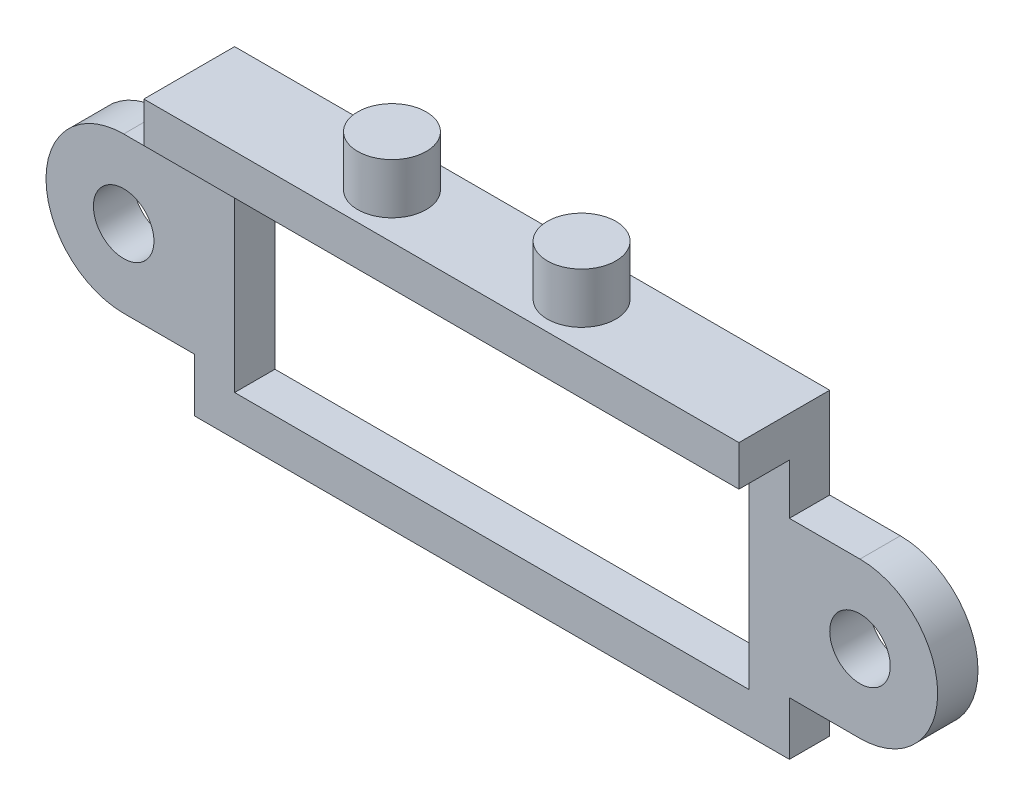
SolidWorks part; units mm, degrees
ref_plane "Front Plane" through (0, 0, 0) normal (0, 0, 1) x (1, 0, 0)
ref_plane "Top Plane" through (0, 0, 0) normal (0, 1, 0) x (1, 0, 0)
ref_plane "Right Plane" through (0, 0, 0) normal (1, 0, 0) x (0, 0, -1)
sketch "Sketch1" plane through (0, 0, 0) normal (0, 0, 1) x (1, 0, 0)
  line L0 (-14.75, 5.675) -> (-14.75, 1.175)
  line L1 (-14.75, -9.175) -> (14.75, -9.175)
  line L2 (-14.75, -6.525) -> (-14.75, -9.175)
  line L3 (-14.75, 5.675) -> (14.75, 5.675)
  line L4 (14.75, 5.675) -> (14.75, 1.175)
  line L5 (-14.75, 1.175) -> (-18.25, 1.175)
  line L6 (-16.75, -2.675) -> (-16.75, -5.5492) construction
  line L7 (-14.75, -6.525) -> (-18.25, -6.525)
  line L8 (0, 5.675) -> (0, -9.175) construction
  line L9 (14.75, 1.175) -> (18.25, 1.175)
  line L10 (14.75, -6.525) -> (18.25, -6.525)
  line L11 (14.75, -6.525) -> (14.75, -9.175)
  line L12 (-12.75, -7.175) -> (12.75, -7.175)
  line L13 (-12.75, -7.175) -> (-12.75, 3.675)
  line L14 (-12.75, 3.675) -> (12.75, 3.675)
  line L15 (12.75, -7.175) -> (12.75, 3.675)
  arc A0 (-18.25, 1.175) -> (-18.25, -6.525) centre (-18.25, -2.675) ccw
  circle A1 centre (-18.25, -2.675) radius 1.5
  arc A2 (18.25, 1.175) -> (18.25, -6.525) centre (18.25, -2.675) cw
  circle A3 centre (18.25, -2.675) radius 1.5
  dimension "D3" = 3
  dimension "D1" = 7.7
  dimension "D2" = 2
  dimension "D4" = 14.75
  dimension "D5" = 2.65
  dimension "D6" = 4.5
  dimension "D7" = 2
  dimension "D8" = 2
  dimension "D9" = 2
  dimension "D10" = 2
extrude "Boss-Extrude1" add sketch "Sketch1" along normal blind 2
sketch "Sketch2" plane through (0, 0, 2) normal (0, 0, 1) x (1, 0, 0)
  line L0 (14.75, 1.175) -> (14.75, 5.675) construction
  line L1 (-14.75, 5.675) -> (14.75, 5.675)
  line L2 (-14.75, 5.675) -> (-14.75, 3.675)
  line L3 (-14.75, 3.675) -> (14.75, 3.675)
  line L4 (14.75, 5.675) -> (14.75, 3.675)
extrude "Boss-Extrude2" add sketch "Sketch2" along normal blind 2.5
sketch "Sketch3" plane through (0, 5.675, 0) normal (0, 1, 0) x (1, 0, 0)
  line L0 (0, 0) -> (0, -4.5) construction
  line L1 (14.75, 0) -> (-14.75, 0) construction
  line L2 (14.75, -4.5) -> (-14.75, -4.5) construction
  line L3 (-3, -2.25) -> (0, -2.25) construction
  line L4 (0, -2.25) -> (3, -2.25) construction
  circle A0 centre (-4.7, -2.25) radius 1.7
  circle A1 centre (4.7, -2.25) radius 1.7
  dimension "D1" = 3.4
  dimension "D2" = 3
extrude "Boss-Extrude3" add sketch "Sketch3" along normal blind 2.5
